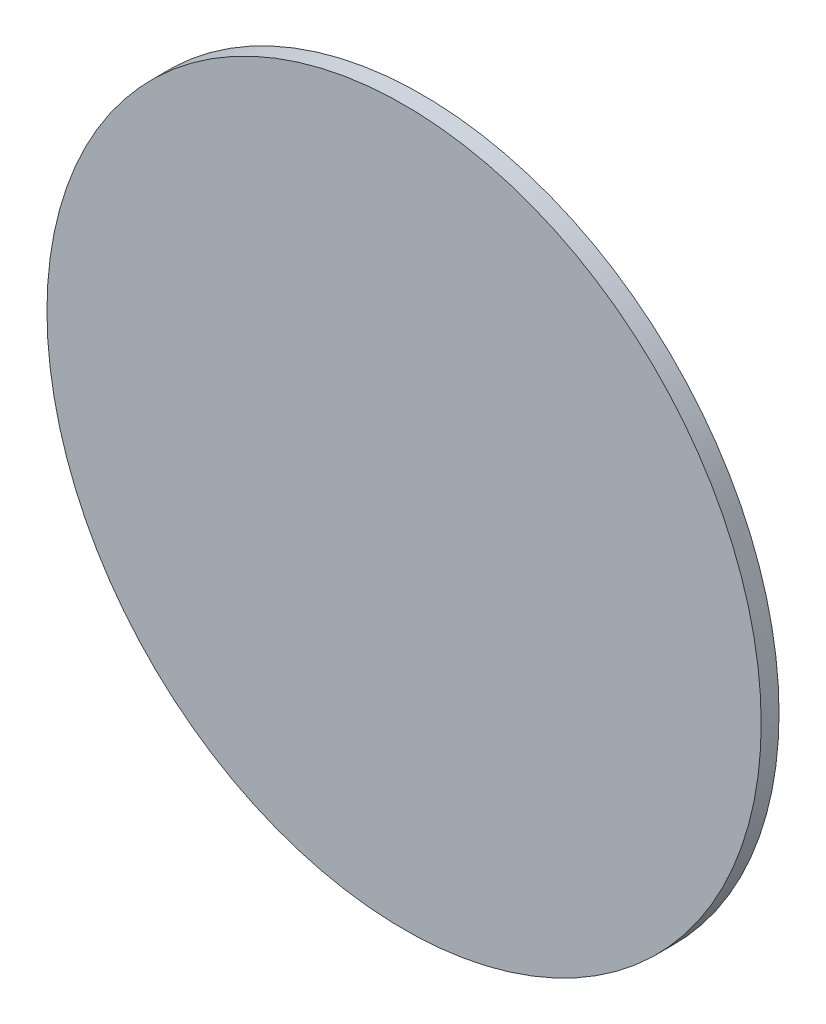
SolidWorks part; units mm, degrees
ref_plane "前视基准面" through (0, 0, 0) normal (0, 0, 1) x (1, 0, 0)
ref_plane "上视基准面" through (0, 0, 0) normal (0, 1, 0) x (1, 0, 0)
ref_plane "右视基准面" through (0, 0, 0) normal (1, 0, 0) x (0, 0, -1)
sketch "草图1" plane through (0, 0, 0) normal (0, 0, 1) x (1, 0, 0)
  circle A0 centre (0, 0) radius 20
extrude "凸台-拉伸1" add sketch "草图1" along normal blind 1
